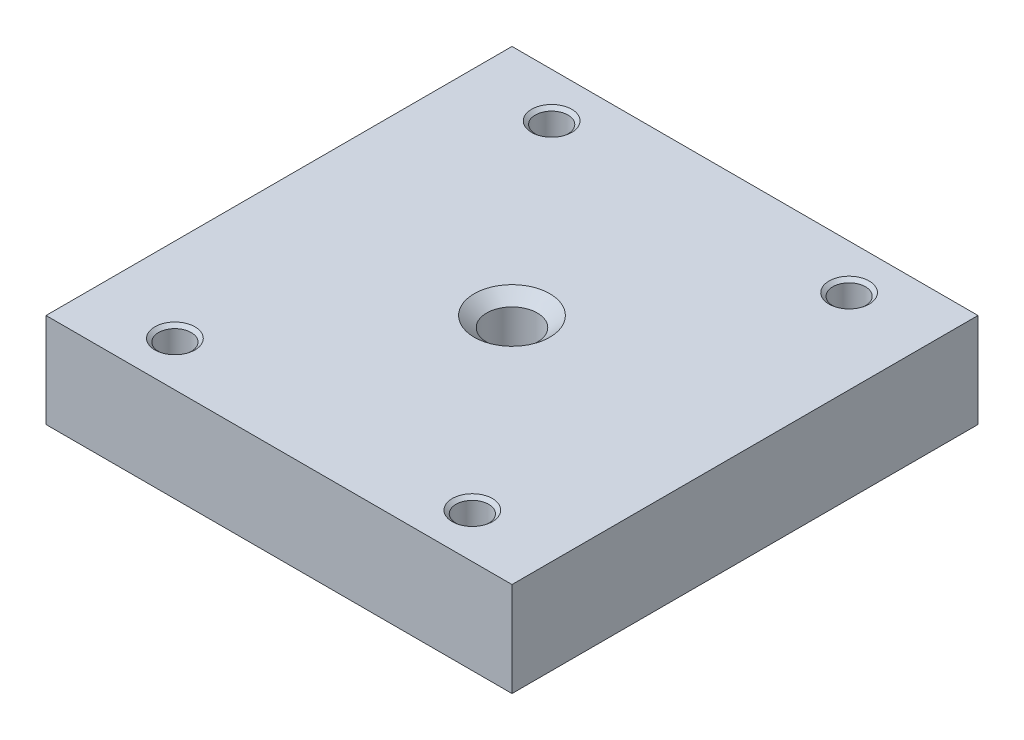
SolidWorks part; units mm, degrees
material "6061 Alloy"
ref_plane "Front" through (0, 0, 0) normal (0, 0, 1) x (1, 0, 0)
ref_plane "Top" through (0, 0, 0) normal (0, 1, 0) x (1, 0, 0)
ref_plane "Right" through (0, 0, 0) normal (1, 0, 0) x (0, 0, -1)
sketch "Sketch1" plane through (0, 0, 0) normal (0, 1, 0) x (1, 0, 0)
  line L1 (0, 0) -> (47, 0)
  line L2 (0, 0) -> (0, 47)
  line L3 (0, 47) -> (47, 47)
  line L4 (47, 0) -> (47, 47)
  dimension "D1" = 47
extrude "Boss-Extrude1" add sketch "Sketch1" along normal blind 9.525
hole_wizard "M4x0.7 Tapped Hole1" positions "Sketch2" profile "Sketch3" tap size "M4x0.7" standard "ANSI Metric" end condition through all
sketch "Sketch2" plane through (0, 9.525, 0) normal (0, 1, 0) x (1, 0, 0)
  line L0 (38.5, 47) -> (38.5, 42.5) construction
  line L1 (47, 47) -> (0, 47) construction
  line L2 (38.5, 42.5) -> (47, 42.5) construction
  line L3 (47, 0) -> (47, 47) construction
  line L5 (8.5, 47) -> (8.5, 42.5) construction
  line L6 (8.5, 42.5) -> (0, 42.5) construction
  line L7 (0, -50) -> (0, 50) construction
  line L8 (8.5, 0) -> (8.5, 4.5) construction
  line L9 (-50, 0) -> (50, 0) construction
  line L10 (8.5, 4.5) -> (0, 4.5) construction
  line L12 (38.5, 0) -> (38.5, 4.5) construction
  line L13 (38.5, 4.5) -> (47, 4.5) construction
  point P0 (38.5, 42.5)
  point P2 (8.5, 42.5)
  point P4 (8.5, 4.5)
  point P6 (38.5, 4.5)
  point P38 (42.0237, 42.9763)
  dimension "D1" = 38
  dimension "D2" = 30
sketch "Sketch3" plane through (38.5, 9.525, -42.5) normal (1, 0, 0) x (0, 0, 1)
  line L0 (0, 0) -> (0, 9.525)
  line L1 (0, 9.525) -> (1.65, 9.525)
  line L2 (1.65, 9.525) -> (1.65, 0.3147)
  line L3 (1.65, 0.3147) -> (2.025, 0)
  line L5 (2.025, 0) -> (0, 0)
  line L6 (-1.65, 0.3147) -> (-2.025, 0) construction
  line L11 (0, -6.35) -> (0, 107.95) construction
  dimension "Thru Tap Drill Dia." = 3.3
  dimension "Thru Tap Drill Depth" = 9.525
  dimension "Near C'Sink Dia." = 4.05
  dimension "Near C'Sink Angle" = 100
cosmetic thread "Hole Thread1"
cosmetic thread "Hole Thread2"
cosmetic thread "Hole Thread3"
cosmetic thread "Hole Thread4"
hole_wizard "1/4-20 Tapped Hole1" positions "Sketch4" profile "Sketch5" tap size "1/4-20" standard "ANSI Inch" end condition through all
sketch "Sketch4" plane through (0, 9.525, 0) normal (0, 1, 0) x (1, 0, 0)
  line L0 (23.5, 47) -> (23.5, 0) construction
  line L1 (47, 47) -> (0, 47) construction
  line L2 (-50, 0) -> (50, 0) construction
  point P0 (23.5, 23.5)
  point P11 (0, 0)
sketch "Sketch5" plane through (23.5, 9.525, -23.5) normal (1, 0, 0) x (0, 0, 1)
  line L0 (0, 0) -> (0, 9.525)
  line L1 (0, 9.525) -> (2.5527, 9.525)
  line L2 (2.5527, 9.525) -> (2.5527, 1.055)
  line L3 (2.5527, 1.055) -> (3.81, 0)
  line L5 (3.81, 0) -> (0, 0)
  line L6 (-2.5527, 1.055) -> (-3.81, 0) construction
  line L11 (0, -6.35) -> (0, 107.95) construction
  dimension "Thru Tap Drill Dia." = 5.1054
  dimension "Thru Tap Drill Depth" = 9.525
  dimension "Near C'Sink Dia." = 7.62
  dimension "Near C'Sink Angle" = 100
cosmetic thread "Hole Thread5" parameters "D2"=6.35
